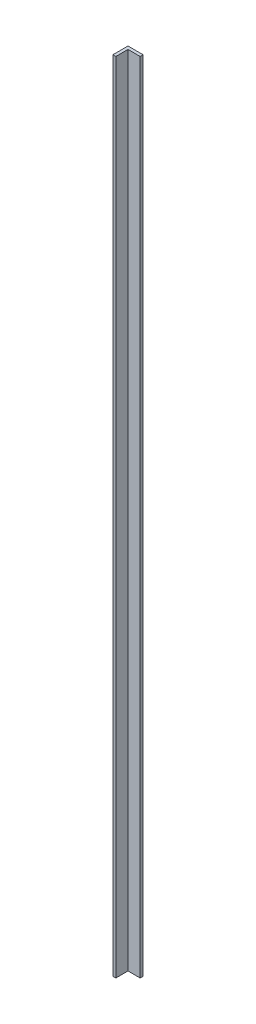
SolidWorks part; units mm, degrees
ref_plane "Front Plane" through (0, 0, 0) normal (0, 0, 1) x (1, 0, 0)
ref_plane "Top Plane" through (0, 0, 0) normal (0, 1, 0) x (1, 0, 0)
ref_plane "Right Plane" through (0, 0, 0) normal (1, 0, 0) x (0, 0, -1)
sketch "Sketch1" plane through (0, 0, 0) normal (0, 1, 0) x (1, 0, 0)
  line L0 (0, 0) -> (6.5, 0)
  line L1 (0, 0) -> (0, -6.5)
  line L4 (-1.5875, 1.5875) -> (6.5, 1.5875)
  line L5 (-1.5875, 1.5875) -> (-1.5875, -6.5)
  line L9 (-1.5875, -6.5) -> (0, -6.5)
  line L10 (6.5, 0) -> (6.5, 1.5875)
  dimension "D1" = 6.5
  dimension "D2" = 6.5
  dimension "D3" = 1.5875
extrude "Boss-Extrude1" add sketch "Sketch1" along normal blind 427.1518
